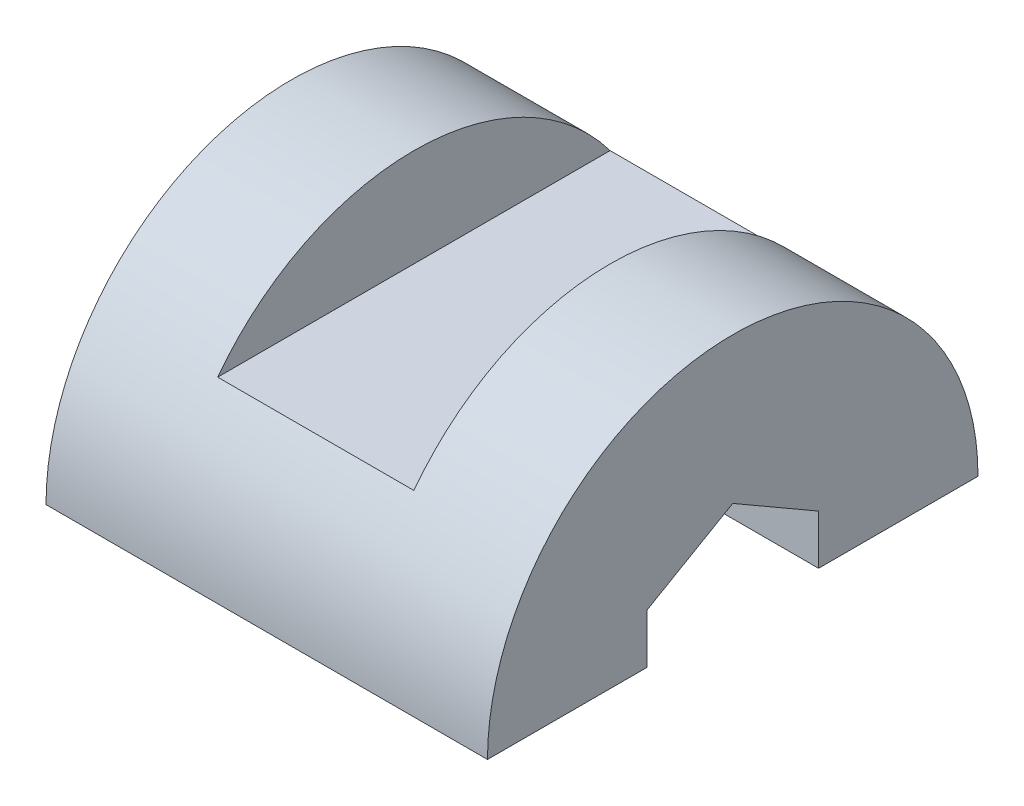
SolidWorks part; units mm, degrees
ref_plane "Front Plane" through (0, 0, 0) normal (0, 0, 1) x (1, 0, 0)
ref_plane "Top Plane" through (0, 0, 0) normal (0, 1, 0) x (1, 0, 0)
ref_plane "Right Plane" through (0, 0, 0) normal (1, 0, 0) x (0, 0, -1)
sketch "Sketch1" plane through (0, 0, 0) normal (1, 0, 0) x (0, 0, -1)
  line L0 (-50, 0) -> (50, 0)
  arc A0 (50, 0) -> (-50, 0) centre (0, 0) ccw
  dimension "D1" = 100
extrude "Boss-Extrude1" add sketch "Sketch1" along normal blind 90
sketch "Sketch2" plane through (0, 0, 0) normal (-1, 0, 0) x (0, 0, 1)
  line L1 (0, 20.2073) -> (-17.5, 10.1036)
  line L2 (-17.5, 10.1036) -> (-17.5, -10.1036)
  line L3 (-17.5, -10.1036) -> (0, -20.2073)
  line L4 (0, -20.2073) -> (17.5, -10.1036)
  line L5 (17.5, -10.1036) -> (17.5, 10.1036)
  line L6 (17.5, 10.1036) -> (0, 20.2073)
  circle A0 centre (0, 0) radius 17.5 construction
  point P1 (0, 0)
  dimension "D1" = 35
extrude "Cut-Extrude1" cut sketch "Sketch2" against normal up to next
sketch "Sketch3" plane through (0, 0, 0) normal (0, 0, 1) x (1, 0, 0)
  line L0 (25, 50) -> (25, 30)
  line L1 (90, 50) -> (0, 50) construction
  line L2 (25, 30) -> (65, 30)
  line L3 (65, 30) -> (65, 50)
  line L4 (65, 50) -> (25, 50)
  line L5 (0, 50) -> (0, 0) construction
  dimension "D1" = 25
  dimension "D2" = 20
  dimension "D3" = 40
extrude "Cut-Extrude2" cut sketch "Sketch3" against normal up to next and the other way up to next
